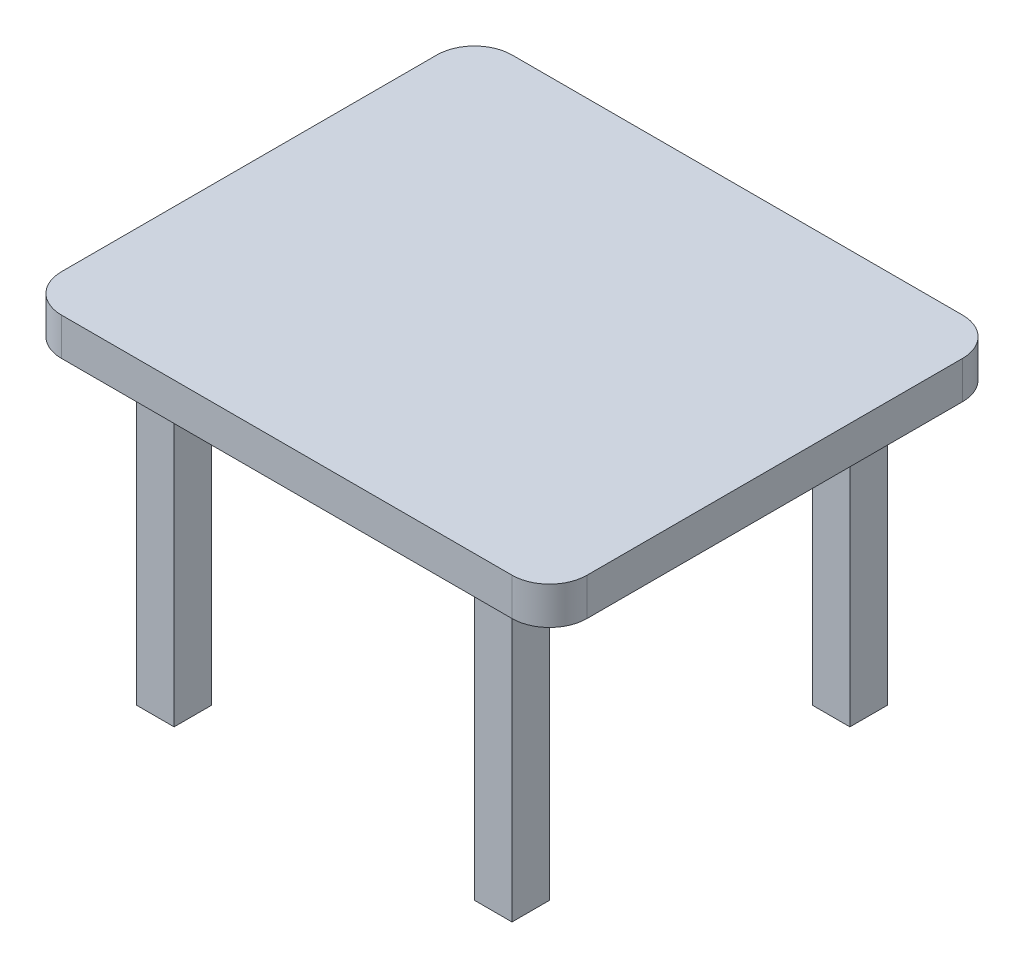
SolidWorks part; units mm, degrees
ref_plane "Front Plane" through (0, 0, 0) normal (0, 0, 1) x (1, 0, 0)
ref_plane "Top Plane" through (0, 0, 0) normal (0, 1, 0) x (1, 0, 0)
ref_plane "Right Plane" through (0, 0, 0) normal (1, 0, 0) x (0, 0, -1)
sketch "Sketch1" plane through (0, 0, 0) normal (0, 1, 0) x (1, 0, 0)
  line L0 (0, 0) -> (-50, 0) construction
  line L1 (-50, 0) -> (-50, 100) construction
  line L2 (-50, 100) -> (0, 100) construction
  line L3 (0, 100) -> (0, 0) construction
  line L4 (0, 0) -> (-10, 0) construction
  line L5 (-10, 0) -> (-10, 10) construction
  line L6 (-10, 10) -> (0, 10) construction
  line L7 (0, 10) -> (0, 90) construction
  line L8 (0, 90) -> (-10, 90) construction
  line L9 (-10, 90) -> (-10, 100) construction
  line L10 (-10, 100) -> (0, 100) construction
  line L11 (-90, 10) -> (-100, 10) construction
  line L12 (-10, 100) -> (0, 100)
  line L13 (-10, 100) -> (-10, 90)
  line L14 (-10, 90) -> (0, 90)
  line L15 (0, 100) -> (0, 90)
  line L16 (-10, 10) -> (0, 10)
  line L17 (-10, 10) -> (-10, 0)
  line L18 (-10, 0) -> (0, 0)
  line L19 (0, 10) -> (0, 0)
  line L20 (-90, 0) -> (-90, 10) construction
  line L21 (-100, 0) -> (-90, 0) construction
  line L22 (-100, 10) -> (-100, 0)
  line L23 (-90, 0) -> (-100, 0)
  line L24 (-90, 10) -> (-90, 0)
  line L25 (-90, 10) -> (-100, 10)
  line L26 (-90, 100) -> (-100, 100) construction
  line L27 (-90, 90) -> (-90, 100) construction
  line L28 (-100, 90) -> (-90, 90) construction
  line L29 (-100, 100) -> (-100, 90)
  line L30 (-90, 90) -> (-100, 90)
  line L31 (-90, 100) -> (-90, 90)
  line L32 (-90, 100) -> (-100, 100)
  dimension "D1" = 10
  dimension "D2" = 10
  dimension "D3" = 100
  dimension "D4" = 10
  dimension "D5" = 10
  dimension "D6" = 50
extrude "Boss-Extrude1" add sketch "Sketch1" along normal blind 80
sketch "Sketch2" plane through (0, 80, 0) normal (0, 1, 0) x (1, 0, 0)
  line L0 (0, 0) -> (0, -10) construction
  line L1 (-120, 110) -> (20, 110)
  line L2 (-120, 110) -> (-120, -10)
  line L3 (-120, -10) -> (20, -10)
  line L4 (20, 110) -> (20, -10)
  line L5 (0, -10) -> (20, -10) construction
  line L6 (-100, 100) -> (-100, 90) construction
  dimension "D1" = 10
  dimension "D2" = 20
  dimension "D3" = 10
  dimension "D4" = 20
extrude "Boss-Extrude2" add sketch "Sketch2" along normal blind 10
fillet "Fillet1" radius 10 4 edges at (-120, 85, -110) (20, 85, -110) (-120, 85, 10) (20, 85, 10)
